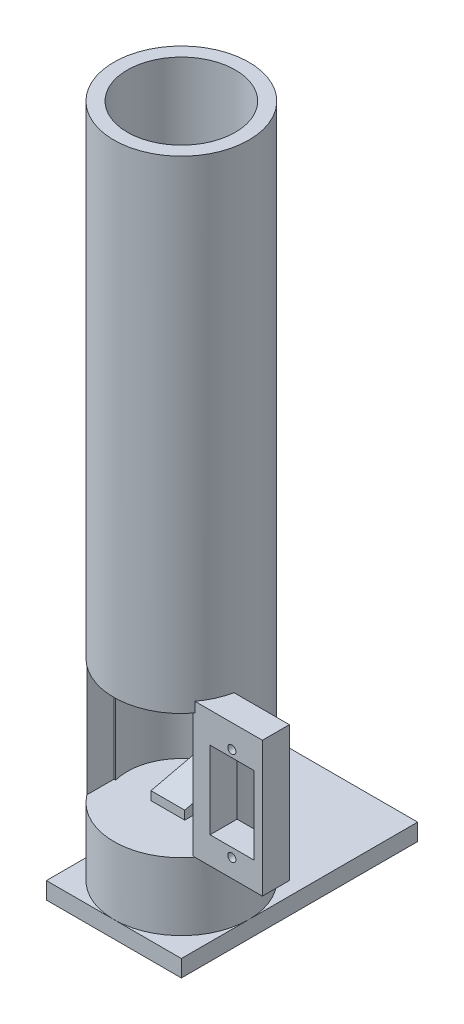
SolidWorks part; units mm, degrees
ref_plane "Front Plane" through (0, 0, 0) normal (0, 0, 1) x (1, 0, 0)
ref_plane "Top Plane" through (0, 0, 0) normal (0, 1, 0) x (1, 0, 0)
ref_plane "Right Plane" through (0, 0, 0) normal (1, 0, 0) x (0, 0, -1)
sketch "Sketch1" plane through (0, 0, 0) normal (0, 1, 0) x (1, 0, 0)
  line L1 (0, 0) -> (40, 0)
  line L2 (0, 0) -> (0, -40)
  line L3 (0, -40) -> (40, -40)
  line L4 (40, 0) -> (40, -40)
  dimension "D1" = 40
  dimension "D2" = 40
extrude "Boss-Extrude1" add sketch "Sketch1" along normal blind 5
sketch "Sketch2" plane through (0, 5, 0) normal (0, 1, 0) x (1, 0, 0)
  line L0 (0, -20) -> (40, -20) construction
  line L1 (0, 0) -> (0, -40) construction
  line L2 (40, -40) -> (40, 0) construction
  line L3 (20, 0) -> (20, -40) construction
  circle A0 centre (20, -20) radius 20
  dimension "D1" = 40
  dimension "D2" = 20
extrude "Boss-Extrude2" add sketch "Sketch2" along normal blind 20
ref_plane "Plane1" through (20, 0, 0) normal (-1, 0, 0) x (0, 0, 1)
sketch "Sketch4" plane through (20, 0, 0) normal (-1, 0, 0) x (0, 0, 1)
  line L0 (35, 25) -> (5, 25)
  line L1 (40, 25) -> (0, 25) construction
  line L2 (5, 25) -> (5, 32)
  line L3 (5, 32) -> (35, 25)
  line L6 (40, 25) -> (0, 25) construction
  dimension "D1" = 30
  dimension "D2" = 7
  dimension "D3" = 5
extrude "Boss-Extrude3" add sketch "Sketch4" along normal mid plane 10
sketch "Sketch6" plane through (0, 25, 0) normal (0, 1, 0) x (1, 0, 0)
  circle A0 centre (20, -20) radius 16
  dimension "D1" = 32
extrude "Extrude-Thin1" add sketch "Sketch6" along normal blind 180 thin
ref_plane "Plane2" through (0, 0, 40) normal (0, 0, 1) x (1, 0, 0)
sketch "Sketch7" plane through (0, 0, 40) normal (0, 0, 1) x (1, 0, 0)
  line L0 (0, 5) -> (0, 0) construction
  line L1 (4, 62) -> (36, 62)
  line L2 (4, 62) -> (4, 25)
  line L3 (4, 25) -> (36, 25)
  line L4 (36, 62) -> (36, 25)
  line L5 (4, 62) -> (36, 25) construction
  line L6 (4, 25) -> (36, 62) construction
  line L7 (0, 0) -> (40, 0) construction
  point P0 (20, 43.5)
  dimension "D1" = 20
  dimension "D2" = 25
  dimension "D3" = 37
  dimension "D4" = 32
extrude "Cut-Extrude1" cut sketch "Sketch7" against normal blind 16
sketch "Sketch8" plane through (36, 0, 0) normal (-1, 0, 0) x (0, 0, 1)
  line L0 (32, 62) -> (32, 25) construction
  line L1 (32, 25) -> (24, 25)
  line L2 (32, 25) -> (32, 65)
  line L3 (32, 65) -> (24, 65)
  line L4 (24, 25) -> (24, 65)
  line L5 (24, 25) -> (24, 62) construction
  line L8 (24, 25) -> (32, 25) construction
  dimension "D1" = 40
extrude "Boss-Extrude4" add sketch "Sketch8" against normal blind 20 and the other way blind 0.5
sketch "Sketch12" plane through (0, 0, 0) normal (0, 0, -1) x (-1, 0, 0)
  line L1 (-40, 5) -> (0, 5)
  line L2 (-40, 5) -> (-40, 0)
  line L3 (-40, 0) -> (0, 0)
  line L4 (0, 5) -> (0, 0)
extrude "Boss-Extrude5" add sketch "Sketch12" along normal blind 30
ref_plane "Plane3" through (35.5, 25, 32) normal (0, 0, 1) x (1, 0, 0)
sketch "Sketch10" plane through (0, 0, 32) normal (0, 0, 1) x (1, 0, 0)
  line L0 (36, 65) -> (56, 65) construction
  line L1 (40.5, 56) -> (53.5, 56)
  line L2 (40.5, 56) -> (40.5, 33)
  line L3 (40.5, 33) -> (53.5, 33)
  line L4 (53.5, 56) -> (53.5, 33)
  line L5 (40.5, 56) -> (53.5, 33) construction
  line L6 (40.5, 33) -> (53.5, 56) construction
  point P0 (47, 44.5)
  dimension "D1" = 13
  dimension "D2" = 23
  dimension "D3" = 9
  dimension "D4" = 9
extrude "Cut-Extrude2" cut sketch "Sketch10" against normal blind 20
sketch "Sketch11" plane through (0, 0, 32) normal (0, 0, 1) x (1, 0, 0)
  circle A0 centre (46.95, 30.4) radius 1.2
  circle A1 centre (46.95, 58.1) radius 1.2
  dimension "D1" = 2.4
  dimension "D2" = 2.4
extrude "Cut-Extrude3" cut sketch "Sketch11" against normal blind 10
